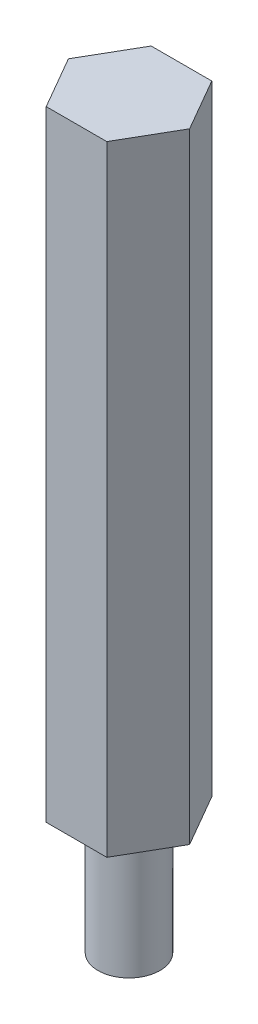
SolidWorks part; units mm, degrees
material "High-leaded brass, UNS C34200"
ref_plane "Front Plane" through (0, 0, 0) normal (0, 0, 1) x (1, 0, 0)
ref_plane "Top Plane" through (0, 0, 0) normal (0, 1, 0) x (1, 0, 0)
ref_plane "Right Plane" through (0, 0, 0) normal (1, 0, 0) x (0, 0, -1)
sketch "스케치1" plane through (0, 0, 0) normal (0, 1, 0) x (1, 0, 0)
  line L1 (1.4665, 2.54) -> (-1.4665, 2.54)
  line L2 (-1.4665, 2.54) -> (-2.9329, 0)
  line L3 (-2.9329, 0) -> (-1.4665, -2.54)
  line L4 (-1.4665, -2.54) -> (1.4665, -2.54)
  line L5 (1.4665, -2.54) -> (2.9329, 0)
  line L6 (2.9329, 0) -> (1.4665, 2.54)
  circle A0 centre (0, 0) radius 2.54 construction
  dimension "D1" = 5.08
extrude "보스-돌출1" add sketch "스케치1" along normal blind 30
sketch "스케치2" plane through (0, 0, 0) normal (0, -1, 0) x (1, 0, 0)
  circle A0 centre (0, 0) radius 1.5
  dimension "D1" = 3
extrude "보스-돌출2" add sketch "스케치2" along normal blind 6
